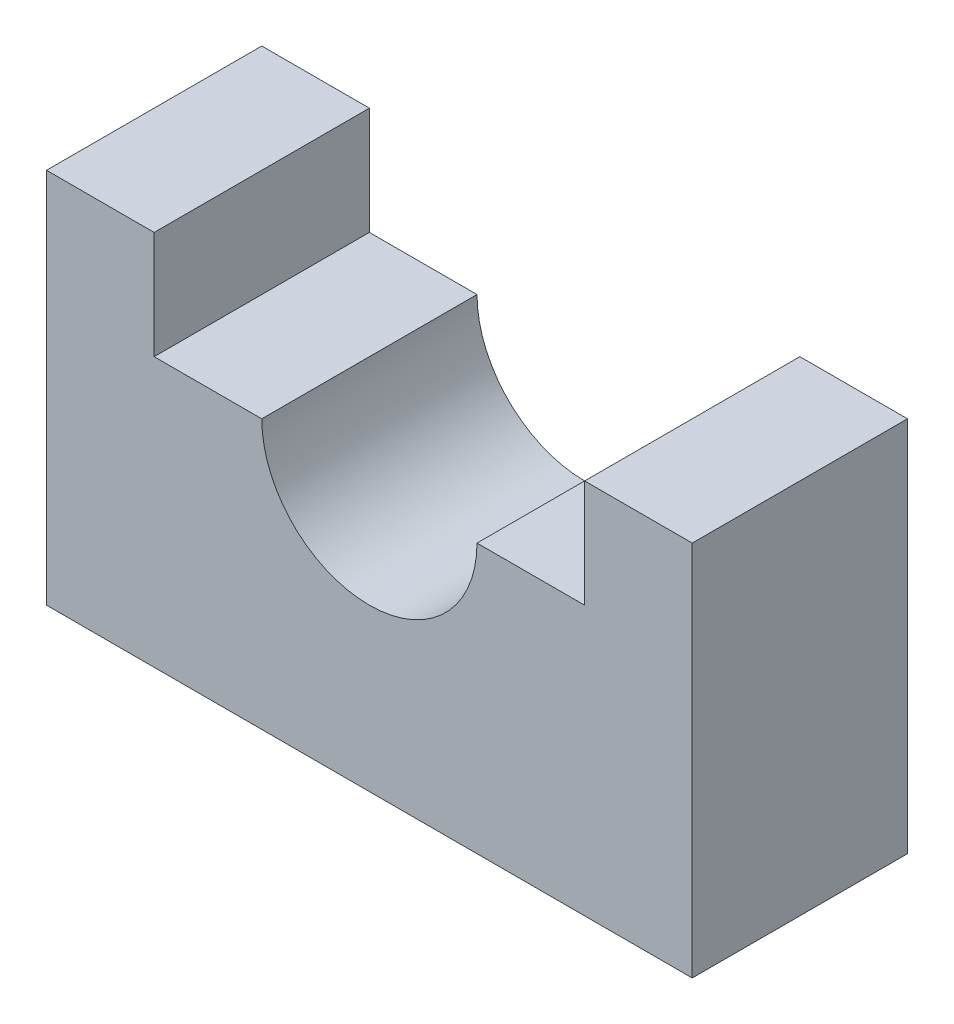
SolidWorks part; units mm, degrees
ref_plane "Front Plane" through (0, 0, 0) normal (0, 0, 1) x (1, 0, 0)
ref_plane "Top Plane" through (0, 0, 0) normal (0, 1, 0) x (1, 0, 0)
ref_plane "Right Plane" through (0, 0, 0) normal (1, 0, 0) x (0, 0, -1)
sketch "Sketch1" plane through (0, 0, 0) normal (0, 0, 1) x (1, 0, 0)
  line L0 (-30, 0) -> (30, 0)
  line L1 (30, 0) -> (30, 35)
  line L2 (30, 35) -> (20, 35)
  line L3 (20, 35) -> (20, 25)
  line L4 (0, 0) -> (0, 60.7759) construction
  line L5 (20, 25) -> (10, 25)
  line L6 (-30, 0) -> (-30, 35)
  line L7 (-30, 35) -> (-20, 35)
  line L8 (-20, 35) -> (-20, 25)
  line L9 (-20, 25) -> (-10, 25)
  arc A0 (-10, 25) -> (10, 25) centre (0, 25) ccw
  dimension "D5" = 10
  dimension "D6" = 20
  dimension "D1" = 30
  dimension "D2" = 35
  dimension "D3" = 10
  dimension "D4" = 10
extrude "Boss-Extrude2" add sketch "Sketch1" along normal blind 20
